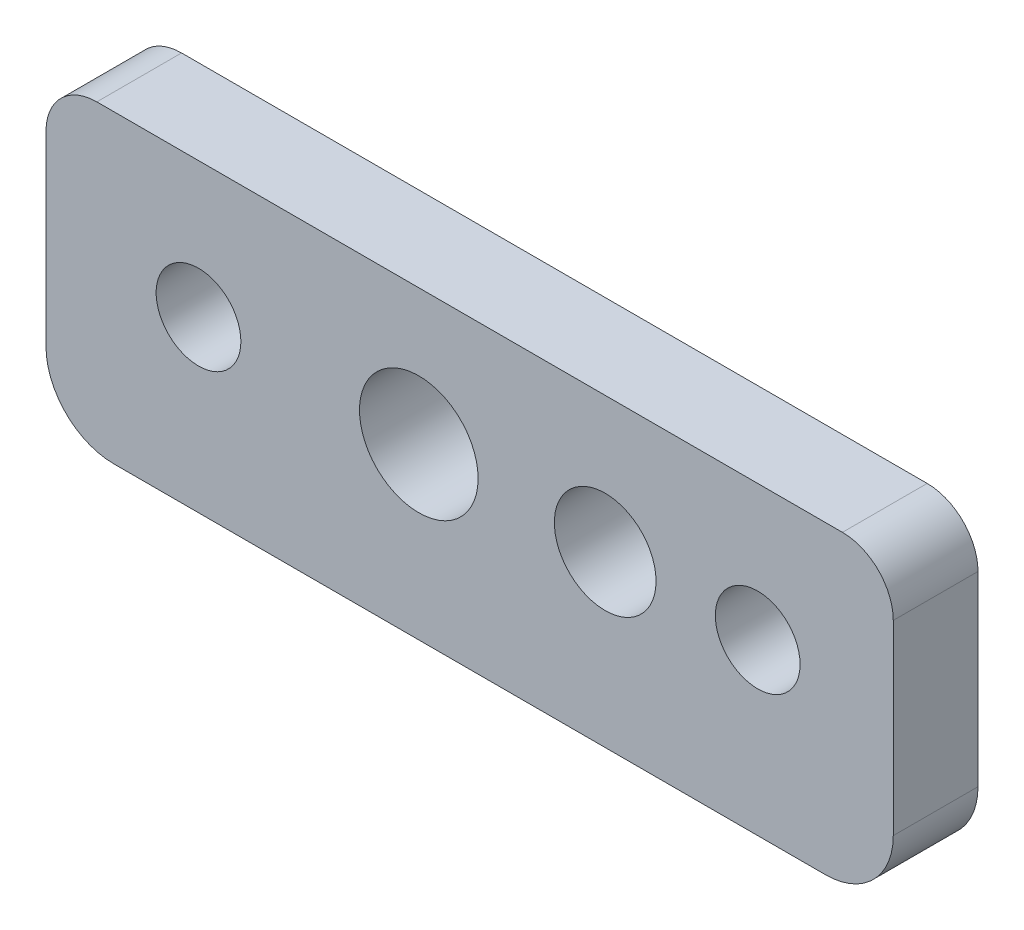
SolidWorks part; units mm, degrees
ref_plane "Alzado" through (0, 0, 0) normal (0, 0, 1) x (1, 0, 0)
ref_plane "Planta" through (0, 0, 0) normal (0, 1, 0) x (1, 0, 0)
ref_plane "Vista lateral" through (0, 0, 0) normal (1, 0, 0) x (0, 0, -1)
sketch "Croquis1" plane through (0, 0, 0) normal (0, 0, 1) x (1, 0, 0)
  line L0 (0, 0) -> (250, 0)
  line L1 (250, 0) -> (250, -90)
  line L2 (250, -90) -> (0, -90)
  line L3 (0, -90) -> (0, 0)
  line L4 (45, 0) -> (45, -40)
  line L5 (45, -40) -> (210, -40) construction
  circle A0 centre (45, -40) radius 12.5
  circle A1 centre (110, -40) radius 17.5
  circle A2 centre (165, -40) radius 15
  circle A3 centre (210, -40) radius 12.5
  point P9 (45, -40)
  point P17 (0, 0)
  dimension "D5" = 25
  dimension "D6" = 35
  dimension "D8" = 25
  dimension "D9" = 30
  dimension "D1" = 90
  dimension "D2" = 250
  dimension "D3" = 40
  dimension "D4" = 45
  dimension "D7" = 65
  dimension "D10" = 55
  dimension "D11" = 45
extrude "Saliente-Extruir1" add sketch "Croquis1" along normal blind 25 contours A0 L5 A1 A2 A3 L1 L0 L4 | L3 L5 A0 L4 L0 | L5 L3 L2 L1 A3 A2 A1 A0
fillet "Redondeo1" radius 15 2 edges at (250, 0, 12.5) (0, 0, 12.5)
fillet "Redondeo2" radius 20 2 edges at (0, -90, 12.5) (250, -90, 12.5)
